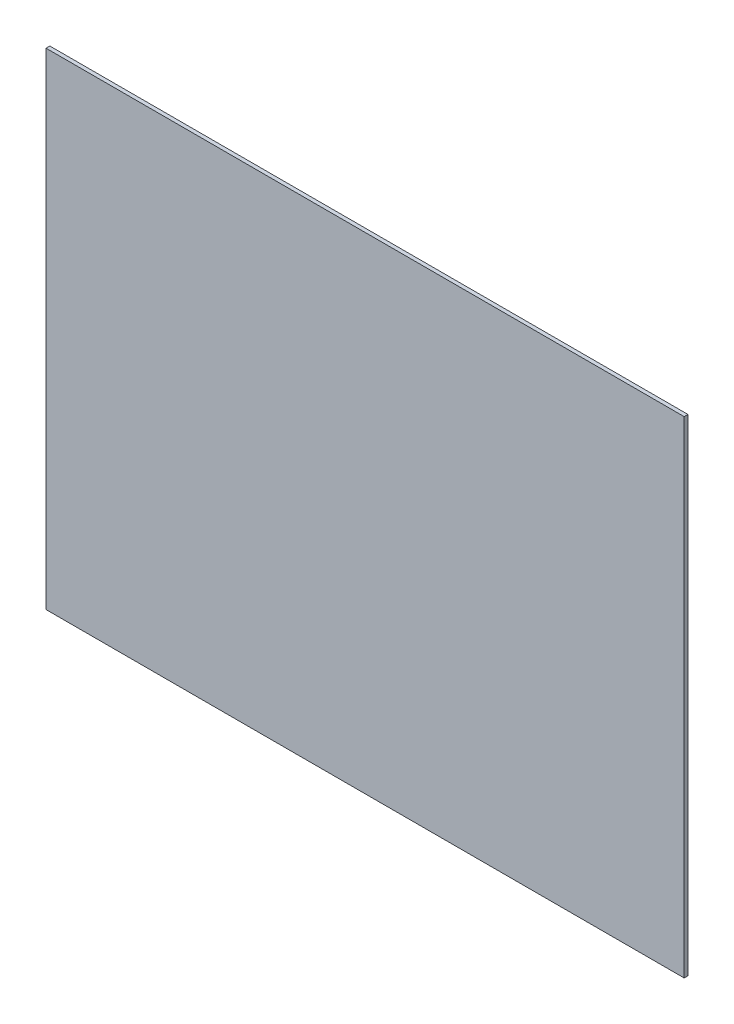
SolidWorks part; units mm, degrees
ref_plane "Front Plane" through (0, 0, 0) normal (0, 0, 1) x (1, 0, 0)
ref_plane "Top Plane" through (0, 0, 0) normal (0, 1, 0) x (1, 0, 0)
ref_plane "Right Plane" through (0, 0, 0) normal (1, 0, 0) x (0, 0, -1)
sketch "Sketch1" plane through (0, 0, 0) normal (0, 0, 1) x (1, 0, 0)
  line L1 (-400.05, -304.8) -> (400.05, -304.8)
  line L2 (-400.05, -304.8) -> (-400.05, 304.8)
  line L3 (-400.05, 304.8) -> (400.05, 304.8)
  line L4 (400.05, -304.8) -> (400.05, 304.8)
  line L5 (-400.05, -304.8) -> (400.05, 304.8) construction
  line L6 (-400.05, 304.8) -> (400.05, -304.8) construction
  point P0 (0, 0)
  dimension "D1" = 800.1
  dimension "D2" = 609.6
extrude "Boss-Extrude1" add sketch "Sketch1" along normal blind 4.7625
